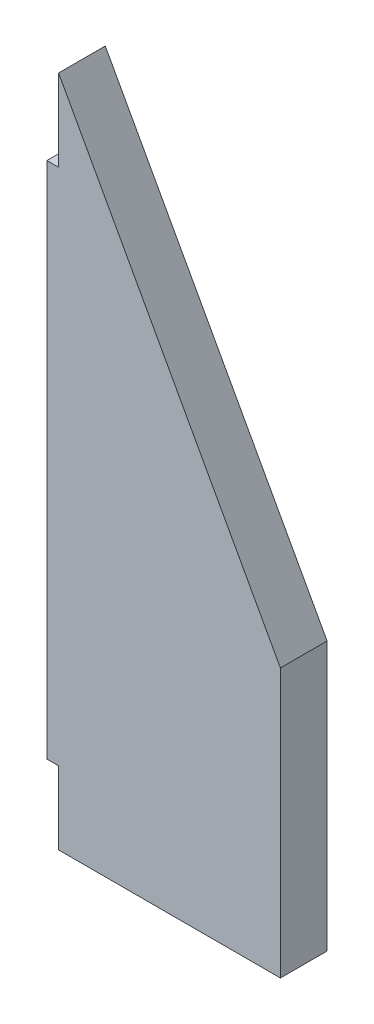
SolidWorks part; units mm, degrees
ref_plane "Front Plane" through (0, 0, 0) normal (0, 0, 1) x (1, 0, 0)
ref_plane "Top Plane" through (0, 0, 0) normal (0, 1, 0) x (1, 0, 0)
ref_plane "Right Plane" through (0, 0, 0) normal (1, 0, 0) x (0, 0, -1)
sketch "Sketch1" plane through (0, 0, 0) normal (0, 0, 1) x (1, 0, 0)
  line L0 (-2.3284, 15.8503) -> (0.2116, 15.8503)
  line L1 (0.2116, 15.8503) -> (0.2116, 0)
  line L4 (0.2116, 0) -> (48.4716, 0)
  line L5 (48.4716, 0) -> (48.4716, 58.42)
  line L6 (48.4716, 58.42) -> (0.2116, 146.3915)
  line L8 (0.2116, 146.3915) -> (0.2116, 128.6263)
  line L11 (0.2116, 128.6263) -> (-2.3284, 128.6263)
  line L12 (-2.3284, 128.6263) -> (-2.3284, 15.8503)
  dimension "D1" = 112.776
  dimension "D2" = 50.8
  dimension "D3" = 2.54
  dimension "D4" = 58.42
extrude "Boss-Extrude1" add sketch "Sketch1" along normal blind 10.16
